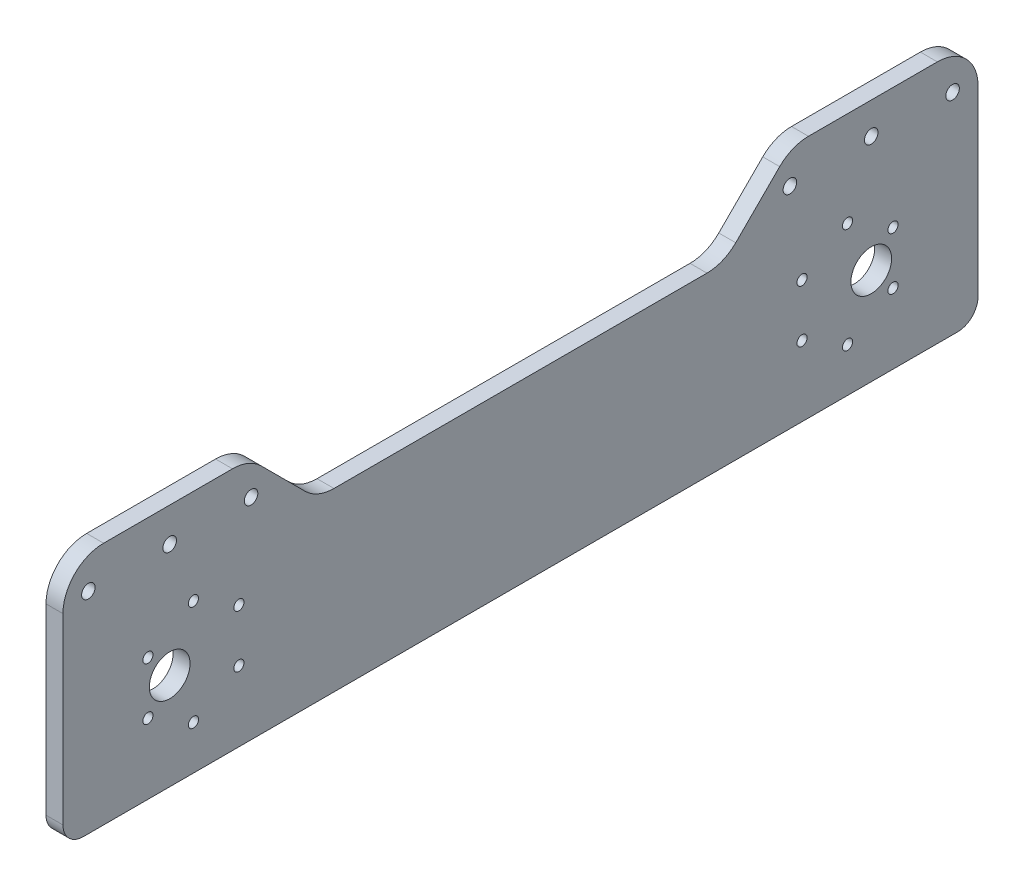
SolidWorks part; units mm, degrees
ref_plane "Front Plane" through (0, 0, 0) normal (0, 0, 1) x (1, 0, 0)
ref_plane "Top Plane" through (0, 0, 0) normal (0, 1, 0) x (1, 0, 0)
ref_plane "Right Plane" through (0, 0, 0) normal (1, 0, 0) x (0, 0, -1)
sketch "Sketch1" plane through (0, 0, 0) normal (1, 0, 0) x (0, 0, -1)
  line L0 (0, 0) -> (55, 0)
  line L1 (270, 0) -> (270, -72)
  line L2 (270, -72) -> (0, -72)
  line L3 (0, -72) -> (0, 0)
  line L4 (20, 0) -> (20, -72) construction
  line L5 (250, 0) -> (250, -72) construction
  line L6 (0, -25) -> (270, -25) construction
  line L7 (135, 0) -> (135, -72) construction
  line L8 (55, 0) -> (75, -20)
  line L9 (38.5, -43.5) -> (31.5, -43.5) construction
  line L10 (0, -10) -> (270, -10) construction
  line L11 (238.5, -43.5) -> (238.5, -9.2765) construction
  line L12 (38.5, -43.5) -> (38.5, -59) construction
  line L13 (75, -20) -> (195, -20)
  line L14 (215, 0) -> (195, -20)
  line L15 (215, 0) -> (270, 0)
  line L16 (55, 0) -> (215, 0) construction
  line L17 (31.5, -43.5) -> (31.5, -10) construction
  circle A0 centre (38.5, -43.5) radius 18.5 construction
  circle A1 centre (31.5, -43.5) radius 6
  circle A3 centre (55.5, -10) radius 2
  circle A4 centre (7.5, -10) radius 2
  circle A5 centre (38.5, -59) radius 1.5
  circle A6 centre (25.0766, -51.25) radius 1.5
  circle A7 centre (25.0766, -35.75) radius 1.5
  circle A8 centre (38.5, -28) radius 1.5
  circle A9 centre (51.9234, -35.75) radius 1.5
  circle A10 centre (51.9234, -51.25) radius 1.5
  circle A11 centre (214.5, -10) radius 2
  circle A12 centre (238.5, -9.2765) radius 2
  circle A13 centre (262.5, -10) radius 2
  circle A14 centre (231.5, -43.5) radius 18.5 construction
  circle A15 centre (244.9234, -35.75) radius 1.5
  circle A16 centre (231.5, -28) radius 1.5
  circle A17 centre (218.0766, -35.75) radius 1.5
  circle A18 centre (218.0766, -51.25) radius 1.5
  circle A19 centre (231.5, -59) radius 1.5
  circle A20 centre (244.9234, -51.25) radius 1.5
  circle A21 centre (238.5, -43.5) radius 6
  circle A22 centre (31.5, -43.5) radius 50 construction
  circle A23 centre (238.5, -43.5) radius 50 construction
  circle A24 centre (31.5, -10) radius 2
  point P66 (135, -20)
  dimension "D8" = 12
  dimension "D10" = 90
  dimension "D11" = 24
  dimension "D13" = 3
  dimension "D15" = 24
  dimension "D18" = 100
  dimension "D3" = 37
  dimension "D17" = 4
  dimension "D1" = 72
  dimension "D2" = 270
  dimension "D4" = 20
  dimension "D5" = 20
  dimension "D6" = 25
  dimension "D7" = 7
  dimension "D9" = 10
  dimension "D12" = 15.5
  dimension "D16" = 90
  dimension "D19" = 20
  dimension "D20" = 135
  dimension "D21" = 120
  dimension "D14" = 6
extrude "Boss-Extrude1" add sketch "Sketch1" along normal blind 5
fillet "Fillet1" radius 6 2 edges at (2.5, -72, 0) (2.5, -72, -270)
fillet "Fillet2" radius 12 6 edges at (2.5, 0, -270) (2.5, 0, 0) (2.5, 0, -215) (2.5, 0, -55) (2.5, -20, -195) (2.5, -20, -75)
